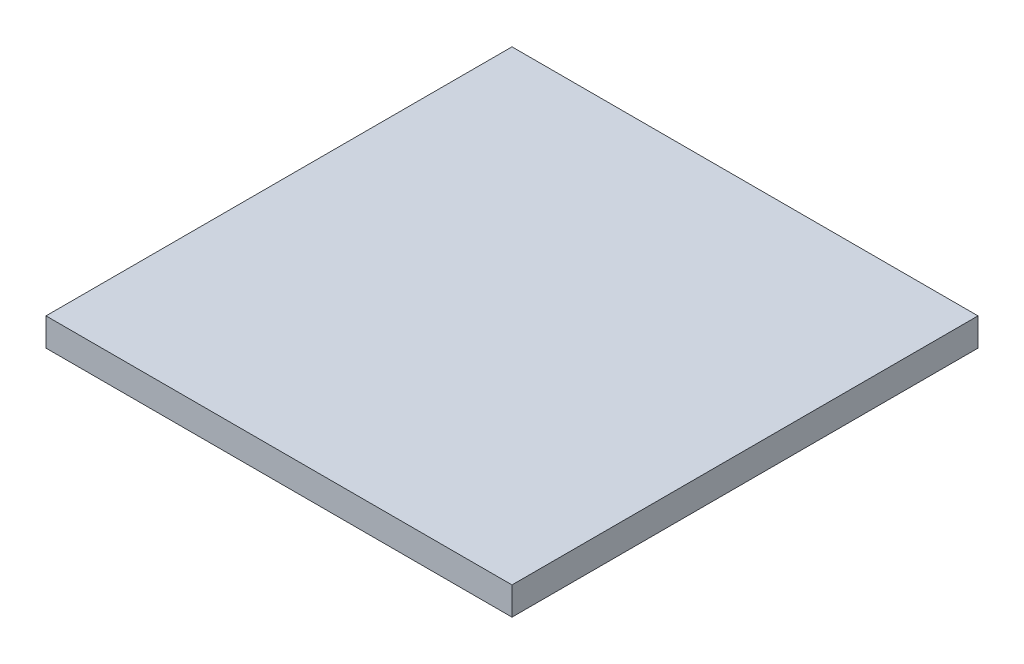
SolidWorks part; units mm, degrees
ref_plane "Front Plane" through (0, 0, 0) normal (0, 0, 1) x (1, 0, 0)
ref_plane "Top Plane" through (0, 0, 0) normal (0, 1, 0) x (1, 0, 0)
ref_plane "Right Plane" through (0, 0, 0) normal (1, 0, 0) x (0, 0, -1)
sketch "Sketch1" plane through (0, 0, 0) normal (0, 0, 1) x (1, 0, 0)
  line L1 (0, 0) -> (500, 0)
  line L2 (0, 0) -> (0, 30)
  line L3 (0, 30) -> (500, 30)
  line L4 (500, 0) -> (500, 30)
  dimension "D1" = 500
  dimension "D2" = 30
extrude "Profile" add sketch "Sketch1" along normal blind 500
equation "\"Profile_Depth\"= 500mm"
equation "\"D1@Profile\" = \"Profile_Depth\""
equation "\"Profile_Sketch_1\"= 500mm"
equation "\"D1@Sketch1\" = \"Profile_Sketch_1\""
equation "\"Profile_Sketch_2\"= 30mm"
equation "\"D2@Sketch1\" = \"Profile_Sketch_2\""
equation "\"EnvelopeWidth\"= 500mm"
equation "\"EnvelopeHeight\"= 30mm"
